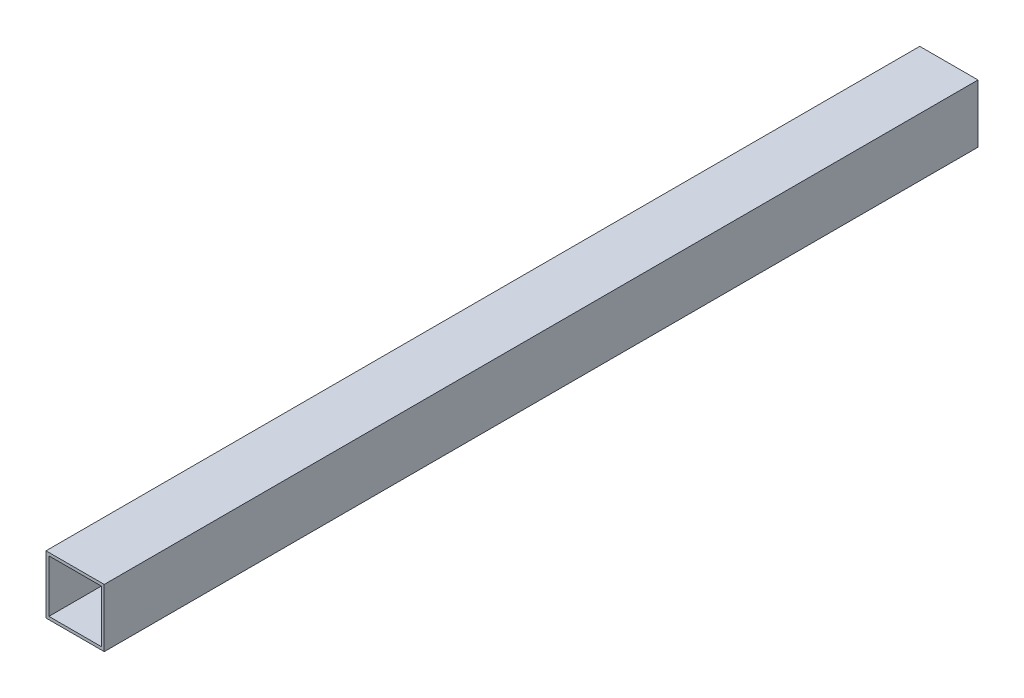
SolidWorks part; units mm, degrees
material "Aleación 1060"
ref_plane "Alzado" through (0, 0, 0) normal (0, 0, 1) x (1, 0, 0)
ref_plane "Planta" through (0, 0, 0) normal (0, 1, 0) x (1, 0, 0)
ref_plane "Vista lateral" through (0, 0, 0) normal (1, 0, 0) x (0, 0, -1)
sketch "Croquis1" plane through (0, 0, 0) normal (0, 0, 1) x (1, 0, 0)
  line L1 (20, -20) -> (-20, -20)
  line L2 (20, -20) -> (20, 20)
  line L3 (20, 20) -> (-20, 20)
  line L4 (-20, -20) -> (-20, 20)
  line L5 (20, -20) -> (-20, 20) construction
  line L6 (20, 20) -> (-20, -20) construction
  point P0 (0, 0)
  dimension "D1" = 40
  dimension "D2" = 40
extrude "Extruir-Lámina1" add sketch "Croquis1" along normal blind 600 thin
